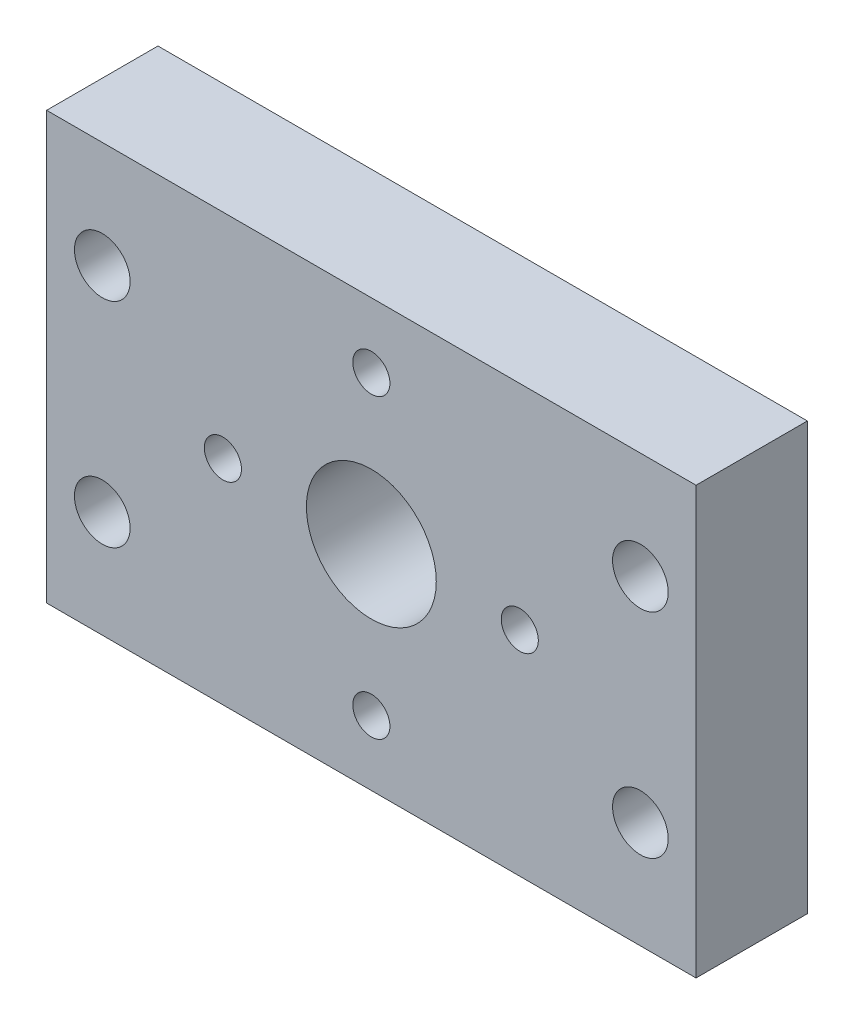
SolidWorks part; units mm, degrees
ref_plane "Plan de face" through (0, 0, 0) normal (0, 0, 1) x (1, 0, 0)
ref_plane "Plan de dessus" through (0, 0, 0) normal (0, 1, 0) x (1, 0, 0)
ref_plane "Plan de droite" through (0, 0, 0) normal (1, 0, 0) x (0, 0, -1)
sketch "Esquisse1" plane through (0, 0, 0) normal (0, 0, 1) x (1, 0, 0)
  line L0 (0, 0) -> (44.4207, 0) construction
  line L1 (17.5, -11.5) -> (-17.5, -11.5)
  line L2 (17.5, -11.5) -> (17.5, 11.5)
  line L3 (17.5, 11.5) -> (-17.5, 11.5)
  line L4 (-17.5, -11.5) -> (-17.5, 11.5)
  line L5 (17.5, -11.5) -> (-17.5, 11.5) construction
  line L6 (17.5, 11.5) -> (-17.5, -11.5) construction
  line L7 (0, 0) -> (0, -37.0394) construction
  line L8 (-11.5, 15) -> (-11.5, -24.3494) construction
  line L10 (-17.5, 11.5) -> (-11.5, 0) construction
  circle A0 centre (0, 0) radius 3.5
  circle A1 centre (0, 8) radius 1
  circle A2 centre (8, 0) radius 1
  circle A3 centre (0, -8) radius 1
  circle A4 centre (-8, 0) radius 1
  circle A5 centre (-14.5, 5.75) radius 1.5
  circle A6 centre (-14.5, -5.75) radius 1.5
  circle A7 centre (14.5, -5.75) radius 1.5
  circle A8 centre (14.5, 5.75) radius 1.5
  point P0 (0, 0)
  dimension "D1" = 7
  dimension "D2" = 2
  dimension "D3" = 2
  dimension "D4" = 2
  dimension "D5" = 2
  dimension "D7" = 8
  dimension "D12" = 3
  dimension "D6" = 8
  dimension "D8" = 8
  dimension "D9" = 8
  dimension "D10" = 35
  dimension "D11" = 23
  dimension "D15" = 3
extrude "Boss.-Extru.1" add sketch "Esquisse1" along normal blind 6 contours L4 L3 L2 L1 | A0 | A1 | A4 | A3 | A2 | A5 | A7 | A6 | A8
sketch "Esquisse2" plane through (0, 0, 6) normal (0, 0, 1) x (1, 0, 0)
  line L0 (17.5, 11.5) -> (-17.5, 11.5) construction
  line L1 (17.5, -11.5) -> (11.5, -11.5)
  line L2 (17.5, -11.5) -> (17.5, 11.5)
  line L3 (17.5, 11.5) -> (11.5, 11.5)
  line L4 (11.5, -11.5) -> (11.5, 11.5)
sketch "Esquisse5" plane through (0, 0, 6) normal (0, 0, 1) x (1, 0, 0)
  line L0 (17.5, 11.5) -> (-17.5, 11.5) construction
  line L1 (-17.5, -11.5) -> (-11.5, -11.5)
  line L2 (-17.5, -11.5) -> (-17.5, 11.5)
  line L3 (-17.5, 11.5) -> (-11.5, 11.5)
  line L4 (-11.5, -11.5) -> (-11.5, 11.5)
